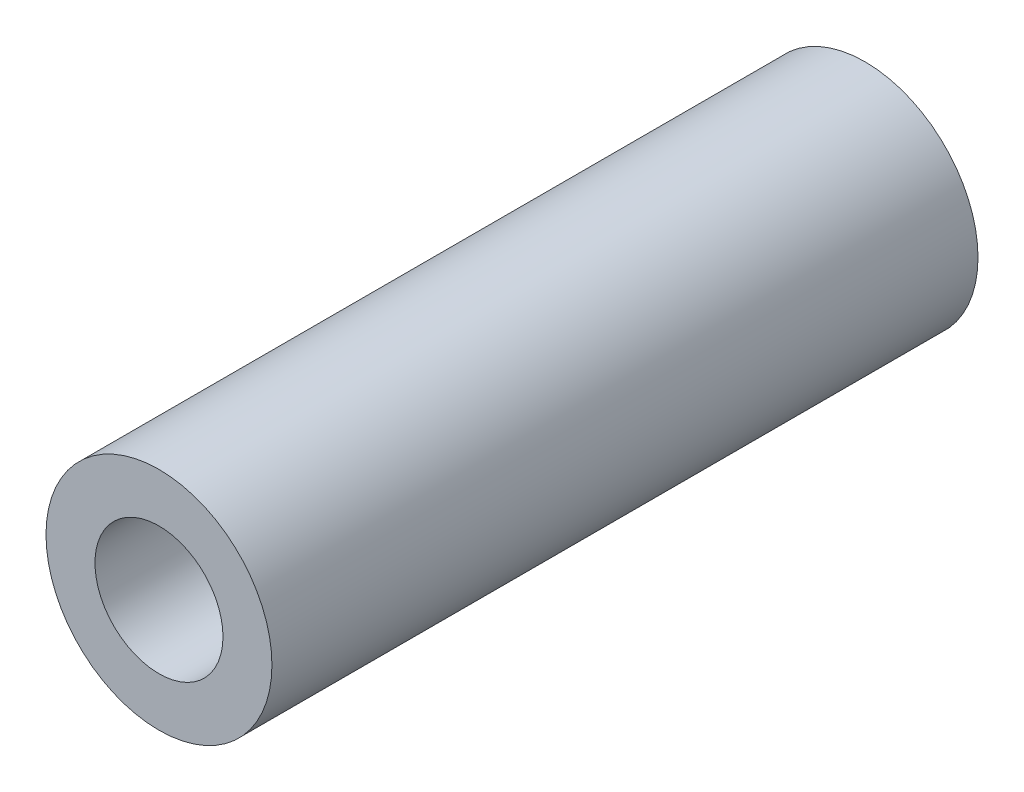
SolidWorks part; units mm, degrees
ref_plane "Front Plane" through (0, 0, 0) normal (0, 0, 1) x (1, 0, 0)
ref_plane "Top Plane" through (0, 0, 0) normal (0, 1, 0) x (1, 0, 0)
ref_plane "Right Plane" through (0, 0, 0) normal (1, 0, 0) x (0, 0, -1)
sketch "Sketch1" plane through (0, 0, 0) normal (0, 0, 1) x (1, 0, 0)
  circle A0 centre (1.9595, 0) radius 3.4
  circle A1 centre (1.9595, 0) radius 6
extrude "Boss-Extrude1" add sketch "Sketch1" against normal up to surface (37.5 mm away)
